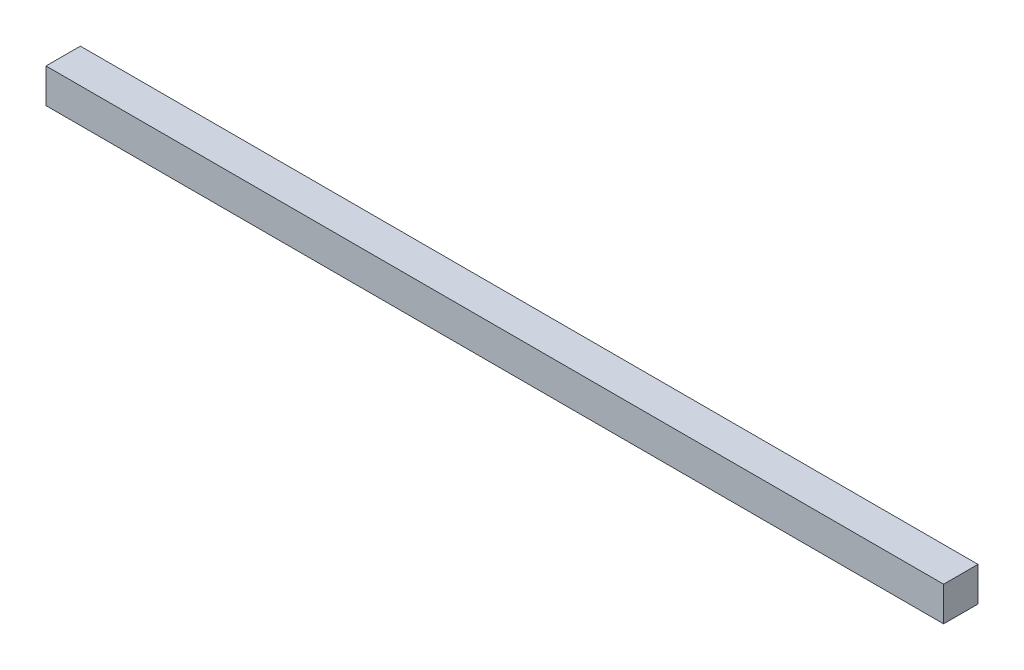
SolidWorks part; units mm, degrees
ref_plane "Front Plane" through (0, 0, 0) normal (0, 0, 1) x (1, 0, 0)
ref_plane "Top Plane" through (0, 0, 0) normal (0, 1, 0) x (1, 0, 0)
ref_plane "Right Plane" through (0, 0, 0) normal (1, 0, 0) x (0, 0, -1)
sketch "Sketch1" plane through (0, 0, 0) normal (0, 0, 1) x (1, 0, 0)
  line L0 (-117.5, 0) -> (117.5, 0) construction
  line L1 (0, -27.7067) -> (0, 27.7067) construction
  dimension "D1" = 235
sketch "Sketch2" plane through (0, 0, 0) normal (1, 0, 0) x (0, 0, -1)
  line L1 (-4.5, -4.5) -> (4.5, -4.5)
  line L2 (-4.5, -4.5) -> (-4.5, 4.5)
  line L3 (-4.5, 4.5) -> (4.5, 4.5)
  line L4 (4.5, -4.5) -> (4.5, 4.5)
  line L5 (-4.5, -4.5) -> (4.5, 4.5) construction
  line L6 (-4.5, 4.5) -> (4.5, -4.5) construction
  point P0 (0, 0)
  dimension "D1" = 9
extrude "Boss-Extrude1" add sketch "Sketch2" along normal up to vertex (117.5 mm away) and the other way up to vertex (117.5 mm away) up to point (117.5, 0, 0) other way up to point (-117.5, 0, 0)
